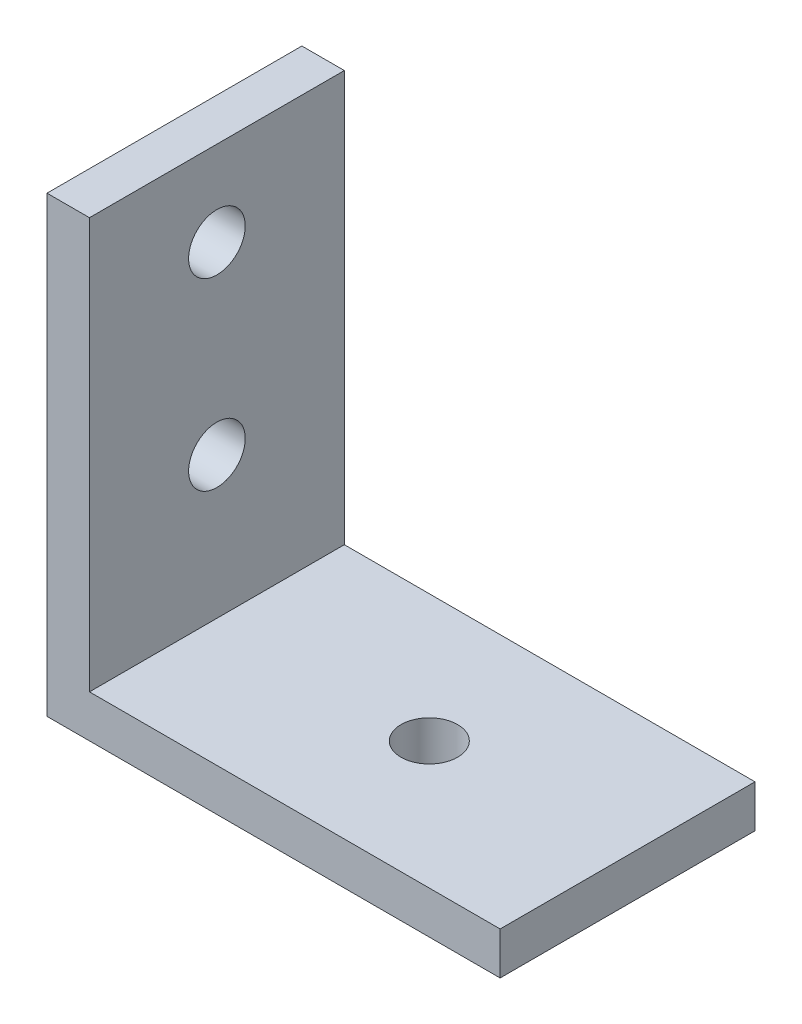
SolidWorks part; units mm, degrees
material "6063-O"
ref_plane "Front Plane" through (0, 0, 0) normal (0, 0, 1) x (1, 0, 0)
ref_plane "Top Plane" through (0, 0, 0) normal (0, 1, 0) x (1, 0, 0)
ref_plane "Right Plane" through (0, 0, 0) normal (1, 0, 0) x (0, 0, -1)
sketch "Sketch1" plane through (0, 0, 0) normal (0, 1, 0) x (1, 0, 0)
  line L1 (0, 0) -> (32, 0)
  line L2 (0, 0) -> (0, 18)
  line L3 (0, 18) -> (32, 18)
  line L4 (32, 0) -> (32, 18)
  dimension "D1" = 18
  dimension "D2" = 32
extrude "Boss-Extrude1" add sketch "Sketch1" along normal blind 3
sketch "Sketch2" plane through (0, 3, 0) normal (0, 1, 0) x (1, 0, 0)
  line L0 (32, 18) -> (0, 18) construction
  line L1 (0, 0) -> (3, 0)
  line L2 (0, 0) -> (0, 18)
  line L3 (0, 18) -> (3, 18)
  line L4 (3, 0) -> (3, 18)
  dimension "D1" = 3
extrude "Boss-Extrude2" add sketch "Sketch2" along normal blind 29
sketch "Sketch3" plane through (0, 3, 0) normal (0, 1, 0) x (1, 0, 0)
  line L1 (32, 0) -> (32, 18) construction
  line L2 (32, 18) -> (3, 18) construction
  circle A0 centre (18, 9) radius 2
  dimension "D1" = 14
  dimension "D3" = 4
  dimension "D2" = 9
extrude "Cut-Extrude1" cut sketch "Sketch3" against normal through all
sketch "Sketch4" plane through (3, 0, 0) normal (1, 0, 0) x (0, 0, -1)
  line L0 (18, 32) -> (18, 3) construction
  line L1 (0, 32) -> (18, 32) construction
  circle A0 centre (9, 26) radius 2
  circle A1 centre (9, 13) radius 2
  dimension "D1" = 9
  dimension "D4" = 4
  dimension "D2" = 6
  dimension "D3" = 19
extrude "Cut-Extrude2" cut sketch "Sketch4" against normal through all
